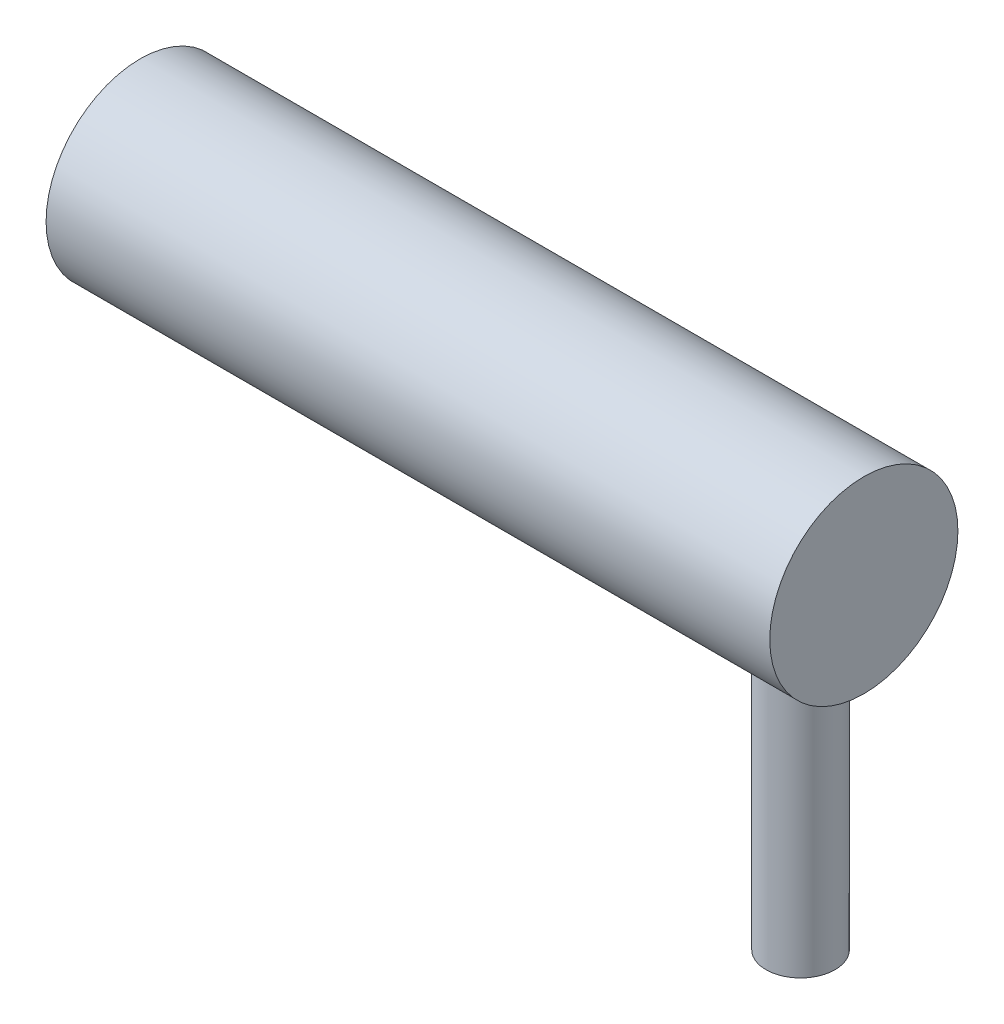
SolidWorks part; units mm, degrees
ref_plane "Front Plane" through (0, 0, 0) normal (0, 0, 1) x (1, 0, 0)
ref_plane "Top Plane" through (0, 0, 0) normal (0, 1, 0) x (1, 0, 0)
ref_plane "Right Plane" through (0, 0, 0) normal (1, 0, 0) x (0, 0, -1)
sketch "Sketch1" plane through (0, 0, 0) normal (1, 0, 0) x (0, 0, -1)
  circle A0 centre (0, 0) radius 26
  dimension "D1" = 52
extrude "Boss-Extrude1" add sketch "Sketch1" along normal mid plane 200
ref_plane "Plane1" through (0, -26, 0) normal (0, -1, 0) x (-1, 0, 0)
sketch "Sketch2" plane through (0, -26, 0) normal (0, -1, 0) x (-1, 0, 0)
  circle A0 centre (-82.5026, 0) radius 9.5458
extrude "Boss-Extrude2" add sketch "Sketch2" along normal blind 70 separate body
